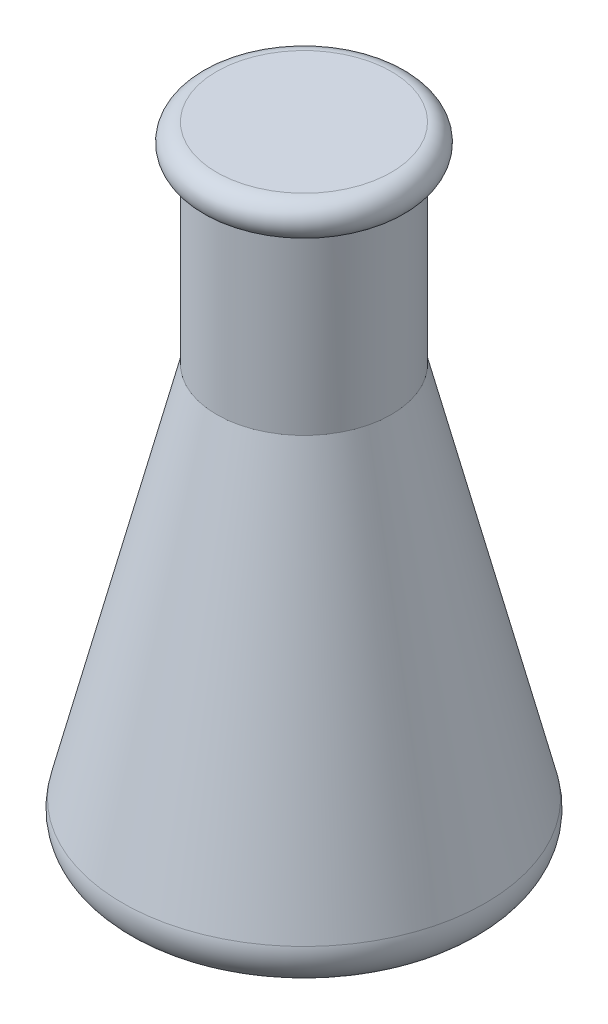
SolidWorks part; units mm, degrees
ref_plane "Płaszczyzna przednia" through (0, 0, 0) normal (0, 0, 1) x (1, 0, 0)
ref_plane "Płaszczyzna górna" through (0, 0, 0) normal (0, 1, 0) x (1, 0, 0)
ref_plane "Płaszczyzna prawa" through (0, 0, 0) normal (1, 0, 0) x (0, 0, -1)
sketch "Sketch1" plane through (0, 0, 0) normal (0, 0, 1) x (1, 0, 0)
  line L0 (0, 41.4229) -> (0, -41.4229) construction
  line L1 (0, 27) -> (0, -27)
  line L2 (0, 27) -> (7.5, 27)
  line L3 (0, -27) -> (16.5, -27)
  line L4 (7.5, 27) -> (7.5, 24)
  line L5 (7.5, 24) -> (7.5, 9)
  line L6 (7.5, 9) -> (16.5, -27)
  arc A0 (7.5, 24) -> (7.5, 27) centre (7.5102, 25.5) ccw
  point P5 (7.5976, 25.5)
  point P8 (0, 0)
  point P12 (7.9065, 25.5)
  point P13 (0, 0)
  dimension "D1" = 54
  dimension "D2" = 7.5
  dimension "D3" = 3
  dimension "D4" = 15
  dimension "D5" = 16.5
revolve "Revolve1" add sketch "Sketch1" angle 360 about L0
fillet "Fillet1" radius 3 1 edges at (-16.5, -27, 0)
